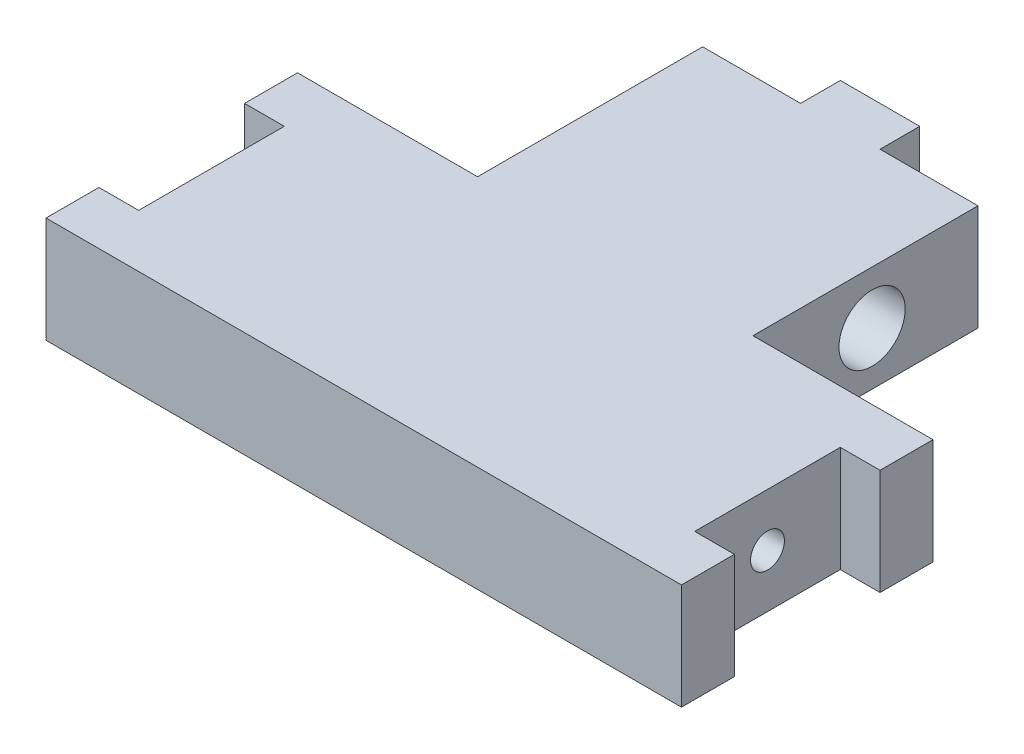
SolidWorks part; units mm, degrees
ref_plane "Front Plane" through (0, 0, 0) normal (0, 0, 1) x (1, 0, 0)
ref_plane "Top Plane" through (0, 0, 0) normal (0, 1, 0) x (1, 0, 0)
ref_plane "Right Plane" through (0, 0, 0) normal (1, 0, 0) x (0, 0, -1)
sketch "Sketch1" plane through (0, 0, 0) normal (0, 1, 0) x (1, 0, 0)
  line L0 (16.51, 0) -> (4.7625, 0)
  line L1 (-16.51, 0) -> (-16.51, -26.9875)
  line L2 (-16.51, -26.9875) -> (-38.1, -26.9875)
  line L3 (-38.1, -26.9875) -> (-38.1, -33.3375)
  line L4 (-38.1, -33.3375) -> (-33.3375, -33.3375)
  line L5 (-33.3375, -33.3375) -> (-33.3375, -50.8)
  line L6 (-33.3375, -50.8) -> (-38.1, -50.8)
  line L7 (-38.1, -50.8) -> (-38.1, -57.15)
  line L8 (-38.1, -57.15) -> (38.1, -57.15)
  line L9 (0, -1000) -> (0, 49000) construction
  line L10 (38.1, -50.8) -> (38.1, -57.15)
  line L11 (33.3375, -50.8) -> (38.1, -50.8)
  line L12 (33.3375, -33.3375) -> (33.3375, -50.8)
  line L13 (38.1, -33.3375) -> (33.3375, -33.3375)
  line L14 (38.1, -26.9875) -> (38.1, -33.3375)
  line L15 (16.51, -26.9875) -> (38.1, -26.9875)
  line L16 (16.51, 0) -> (16.51, -26.9875)
  line L17 (4.7625, 0) -> (4.7625, 4.7625)
  line L18 (4.7625, 4.7625) -> (-4.7625, 4.7625)
  line L19 (-4.7625, 0) -> (-4.7625, 4.7625)
  line L20 (-16.51, 0) -> (-4.7625, 0)
  point P15 (0, -57.15)
  point P25 (0, 4.7625)
  point P26 (0, 0)
  dimension "D1" = 26.9875
  dimension "D2" = 33.02
  dimension "D3" = 6.35
  dimension "D4" = 6.35
  dimension "D5" = 66.675
  dimension "D6" = 76.2
  dimension "D7" = 9.525
  dimension "D8" = 4.7625
  dimension "D9" = 57.15
extrude "Boss-Extrude1" add sketch "Sketch1" along normal blind 12.7
sketch "Sketch2" plane through (33.3375, 0, 0) normal (1, 0, 0) x (0, 0, -1)
  line L0 (-50.8, 12.7) -> (-50.8, 0) construction
  line L1 (-50.8, 0) -> (-33.3375, 0) construction
  line L3 (0, 12.7) -> (0, 0) construction
  circle A0 centre (-42.0688, 6.35) radius 2.032
  circle A1 centre (-12.7, 6.35) radius 3.9688
  point P6 (-50.8, 6.35)
  point P9 (-42.0688, 0)
  dimension "D1" = 7.9375
  dimension "D2" = 4.064
  dimension "D3" = 12.7
extrude "Cut-Extrude1" cut sketch "Sketch2" against normal through all
sketch "Sketch3" plane through (0, 0, 0) normal (0, 0, -1) x (-1, 0, 0)
  line L3 (-16.51, 12.7) -> (-16.51, 0) construction
  line L4 (-16.51, 0) -> (-4.7625, 0) construction
  line L5 (16.51, 12.7) -> (16.51, 0) construction
  circle A0 centre (-10.16, 6.35) radius 1.1303
  circle A1 centre (10.16, 6.35) radius 1.1303
  dimension "D3" = 2.2606
  dimension "D1" = 6.35
  dimension "D2" = 6.35
  dimension "D4" = 6.35
extrude "Cut-Extrude2" cut sketch "Sketch3" against normal blind 4.7625
